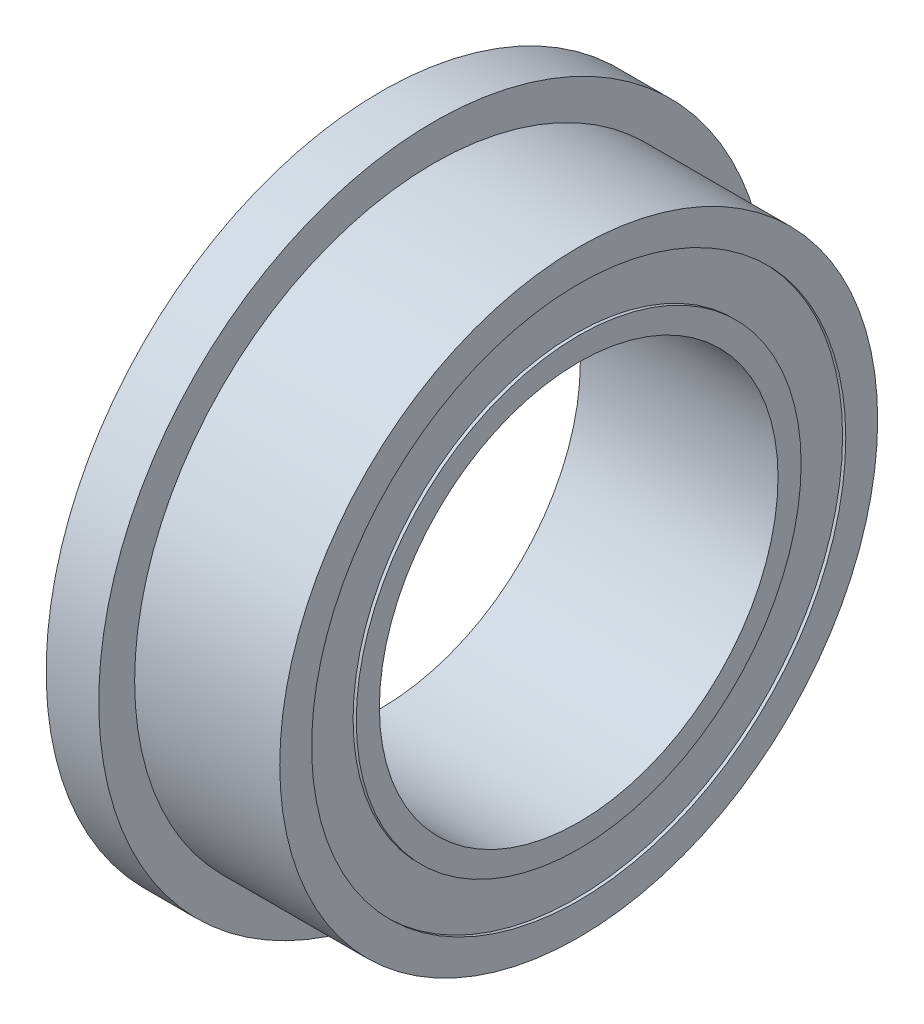
SolidWorks part; units mm, degrees
ref_plane "Front Plane" through (0, 0, 0) normal (0, 0, 1) x (1, 0, 0)
ref_plane "Top Plane" through (0, 0, 0) normal (0, 1, 0) x (1, 0, 0)
ref_plane "Right Plane" through (0, 0, 0) normal (1, 0, 0) x (0, 0, -1)
sketch "Sketch1" plane through (0, 0, 0) normal (1, 0, 0) x (0, 0, -1)
  circle A0 centre (0, 0) radius 5.334
  dimension "D1" = 10.668
extrude "Boss-Extrude1" add sketch "Sketch1" along normal blind 0.8382
sketch "Sketch2" plane through (0.8382, 0, 0) normal (1, 0, 0) x (0, 0, -1)
  circle A0 centre (0, 0) radius 4.7625
  dimension "D1" = 9.525
extrude "Boss-Extrude2" add sketch "Sketch2" along normal offset from surface (2.3114 mm away) 3.1496 up to face at (0, 0, -5.334)
sketch "Sketch3" plane through (3.1496, 0, 0) normal (1, 0, 0) x (0, 0, -1)
  circle A0 centre (0, 0) radius 3.175
  dimension "D1" = 6.35
extrude "Cut-Extrude1" cut sketch "Sketch3" against normal through all
sketch "Sketch4" plane through (0, 0, 0) normal (-1, 0, 0) x (0, 0, 1)
  circle A0 centre (0, 0) radius 3.5433
  circle A1 centre (0, 0) radius 4.4069
  dimension "D1" = 8.8138
  dimension "D2" = 7.0866
extrude "Cut-Extrude2" cut sketch "Sketch4" against normal blind 0.0508
sketch "Sketch5" plane through (3.1496, 0, 0) normal (1, 0, 0) x (0, 0, -1)
  circle A0 centre (0, 0) radius 3.5433
  circle A1 centre (0, 0) radius 4.2545
  dimension "D1" = 7.0866
  dimension "D2" = 8.509
extrude "Cut-Extrude3" cut sketch "Sketch5" against normal blind 0.0508
